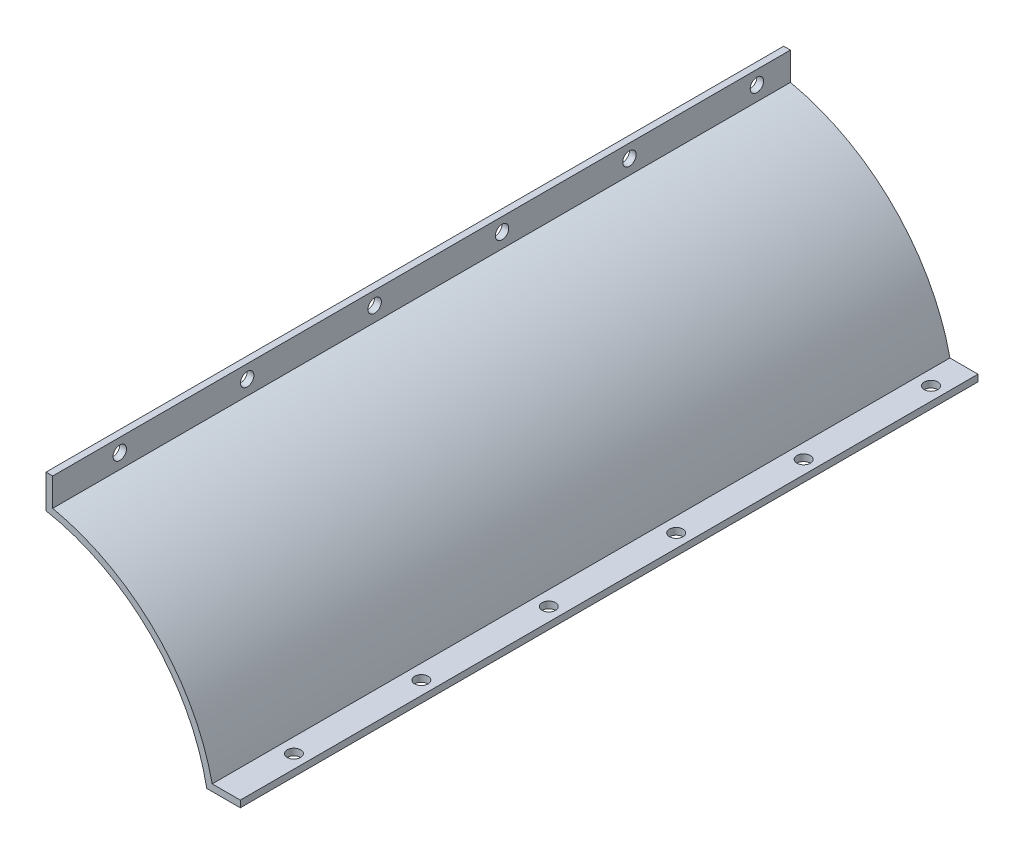
SolidWorks part; units mm, degrees
ref_plane "Front Plane" through (0, 0, 0) normal (0, 0, 1) x (1, 0, 0)
ref_plane "Top Plane" through (0, 0, 0) normal (0, 1, 0) x (1, 0, 0)
ref_plane "Right Plane" through (0, 0, 0) normal (1, 0, 0) x (0, 0, -1)
sketch "Sketch2" plane through (0, 0, 0) normal (0, 0, 1) x (1, 0, 0)
  line L0 (76.9235, 16.8156) -> (87.5508, 16.8156)
  line L1 (16.51, 87.6085) -> (16.51, 76.9897)
  line L2 (13.97, 87.6085) -> (13.97, 74.9085)
  line L3 (16.51, 87.6085) -> (13.97, 87.6085)
  line L4 (87.5508, 16.8156) -> (87.5508, 14.2756)
  line L7 (74.8508, 14.2756) -> (87.5508, 14.2756)
  arc A2 (74.8508, 14.2756) -> (13.97, 74.9085) centre (0, 0) ccw
  arc A3 (76.9235, 16.8156) -> (16.51, 76.9897) centre (0, 0) ccw
  point P6 (0, 76.2)
  point P7 (0, 76.2)
  point P10 (13.97, 76.2)
  point P15 (76.2, 0)
  point P18 (76.2, -13.97)
  point P19 (0, 0)
  dimension "D1" = 2.54
  dimension "D3" = 76.2
  dimension "D2" = 12.7
  dimension "D4" = 12.7
extrude "Boss-Extrude1" add sketch "Sketch2" along normal blind 279.4 contours L0 A3 L1 L3 L2 A2 L7 L4
sketch "Sketch3" plane through (16.51, 0, 0) normal (1, 0, 0) x (0, 0, -1)
  line L0 (0, 87.6085) -> (0, 76.9897) construction
  line L1 (-279.4, 87.6085) -> (0, 87.6085) construction
  circle A0 centre (-12.7, 82.5285) radius 2.54
  circle A1 centre (-60.96, 82.5285) radius 2.54
  circle A2 centre (-109.22, 82.5285) radius 2.54
  circle A3 centre (-157.48, 82.5285) radius 2.54
  circle A4 centre (-205.74, 82.5285) radius 2.54
  circle A5 centre (-254, 82.5285) radius 2.54
  dimension "D1" = 12.7
  dimension "D2" = 5.08
  dimension "D3" = 6
extrude "Cut-Extrude1" cut sketch "Sketch3" against normal blind 279.4
sketch "Sketch4" plane through (0, 14.2756, 0) normal (0, -1, 0) x (1, 0, 0)
  line L0 (87.5508, 279.4) -> (87.5508, 0) construction
  line L1 (74.8508, 0) -> (87.5508, 0) construction
  circle A0 centre (82.4708, 12.7) radius 2.54
  circle A1 centre (82.4708, 60.96) radius 2.54
  circle A2 centre (82.4708, 109.22) radius 2.54
  circle A3 centre (82.4708, 157.48) radius 2.54
  circle A4 centre (82.4708, 205.74) radius 2.54
  circle A5 centre (82.4708, 254) radius 2.54
  dimension "D1" = 5.08
  dimension "D2" = 12.7
  dimension "D3" = 6
extrude "Cut-Extrude2" cut sketch "Sketch4" against normal blind 279.4
